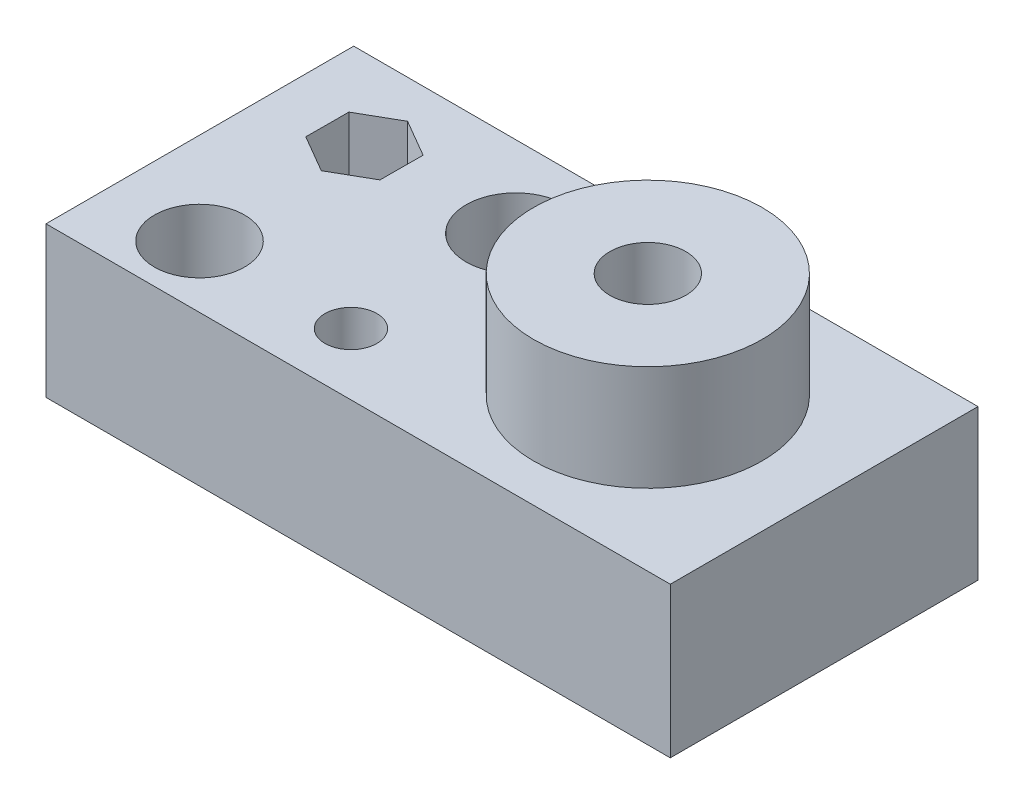
SolidWorks part; units mm, degrees
ref_plane "Front Plane" through (0, 0, 0) normal (0, 0, 1) x (1, 0, 0)
ref_plane "Top Plane" through (0, 0, 0) normal (0, 1, 0) x (1, 0, 0)
ref_plane "Right Plane" through (0, 0, 0) normal (1, 0, 0) x (0, 0, -1)
sketch "Sketch1" plane through (0, 0, 0) normal (0, 1, 0) x (1, 0, 0)
  line L5 (-6.1077, 5.394) -> (35.4018, 5.394)
  line L6 (-6.1077, 5.394) -> (-6.1077, -15.0659)
  line L7 (2.4802, 1.4199) -> (0.0104, 2.8579)
  line L8 (0.0104, 2.8579) -> (-2.4698, 1.4379)
  line L9 (-2.4698, 1.4379) -> (-2.4802, -1.4199)
  line L10 (-2.4802, -1.4199) -> (-0.0104, -2.8579)
  line L11 (-0.0104, -2.8579) -> (2.4698, -1.4379)
  line L12 (2.4698, -1.4379) -> (2.4802, 1.4199)
  line L13 (-6.1077, -15.0659) -> (35.4018, -15.0659)
  line L14 (35.4018, 5.394) -> (35.4018, -15.0659)
  circle A0 centre (0, 0) radius 2.475 construction
  circle A1 centre (-0.0101, -10.9574) radius 3
  circle A2 centre (10.0606, 0) radius 3.3
  circle A3 centre (10.0606, -10.9574) radius 1.725
  point P0 (0, 0)
  point P7 (2.475, -0.009)
  dimension "D4" = 6
  dimension "D1" = 6.6
  dimension "D2" = 3.45
  dimension "D3" = 4.95
extrude "Boss-Extrude1" add sketch "Sketch1" along normal blind 10
sketch "Sketch2" plane through (0, 10, 0) normal (0, 1, 0) x (1, 0, 0)
  circle A0 centre (23.7601, -4.9172) radius 7.6
  dimension "D1" = 15.2
extrude "Boss-Extrude2" add sketch "Sketch2" along normal blind 7
sketch "Sketch3" plane through (0, 17, 0) normal (0, 1, 0) x (1, 0, 0)
  circle A0 centre (23.7601, -4.9172) radius 2.525
  dimension "D1" = 5.05
extrude "Cut-Extrude1" cut sketch "Sketch3" against normal through all
